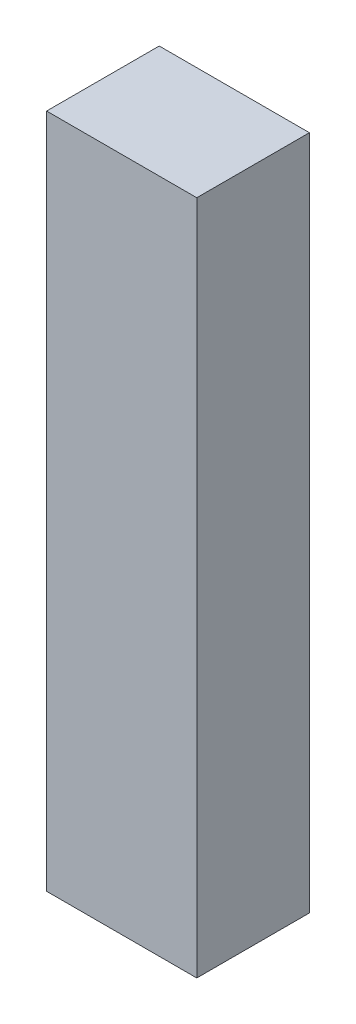
SolidWorks part; units mm, degrees
material "1060-H18 Rod (SS)"
ref_plane "Front Plane" through (0, 0, 0) normal (0, 0, 1) x (1, 0, 0)
ref_plane "Top Plane" through (0, 0, 0) normal (0, 1, 0) x (1, 0, 0)
ref_plane "Right Plane" through (0, 0, 0) normal (1, 0, 0) x (0, 0, -1)
sketch "Sketch1" plane through (0, 0, 0) normal (0, 1, 0) x (1, 0, 0)
  line L1 (50, -37.5) -> (-50, -37.5)
  line L2 (50, -37.5) -> (50, 37.5)
  line L3 (50, 37.5) -> (-50, 37.5)
  line L4 (-50, -37.5) -> (-50, 37.5)
  line L5 (50, -37.5) -> (-50, 37.5) construction
  line L6 (50, 37.5) -> (-50, -37.5) construction
  point P0 (0, 0)
  dimension "D1" = 75
  dimension "D2" = 100
extrude "Boss-Extrude1" add sketch "Sketch1" along normal blind 450
